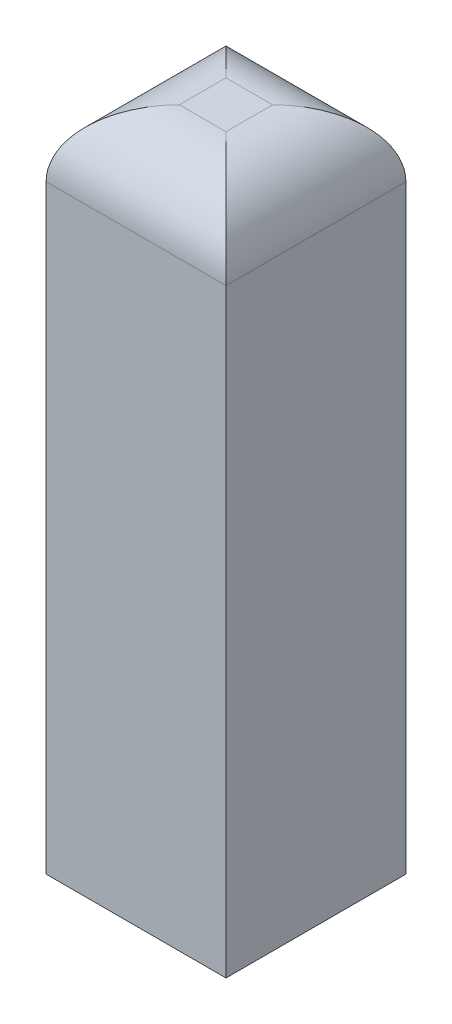
SolidWorks part; units mm, degrees
ref_plane "Front Plane" through (0, 0, 0) normal (0, 0, 1) x (1, 0, 0)
ref_plane "Top Plane" through (0, 0, 0) normal (0, 1, 0) x (1, 0, 0)
ref_plane "Right Plane" through (0, 0, 0) normal (1, 0, 0) x (0, 0, -1)
sketch "Sketch1" plane through (0, 0, 0) normal (0, 1, 0) x (1, 0, 0)
  line L1 (-1.35, 1.35) -> (1.35, 1.35)
  line L2 (-1.35, 1.35) -> (-1.35, -1.35)
  line L3 (-1.35, -1.35) -> (1.35, -1.35)
  line L4 (1.35, 1.35) -> (1.35, -1.35)
  line L5 (-1.35, 1.35) -> (1.35, -1.35) construction
  line L6 (-1.35, -1.35) -> (1.35, 1.35) construction
  point P0 (0, 0)
  dimension "D1" = 2.7
extrude "Boss-Extrude1" add sketch "Sketch1" along normal blind 10
fillet "Fillet1" radius 1 4 edges at (0, 10, 1.35) (-1.35, 10, 0) (0, 10, -1.35) (1.35, 10, 0)
